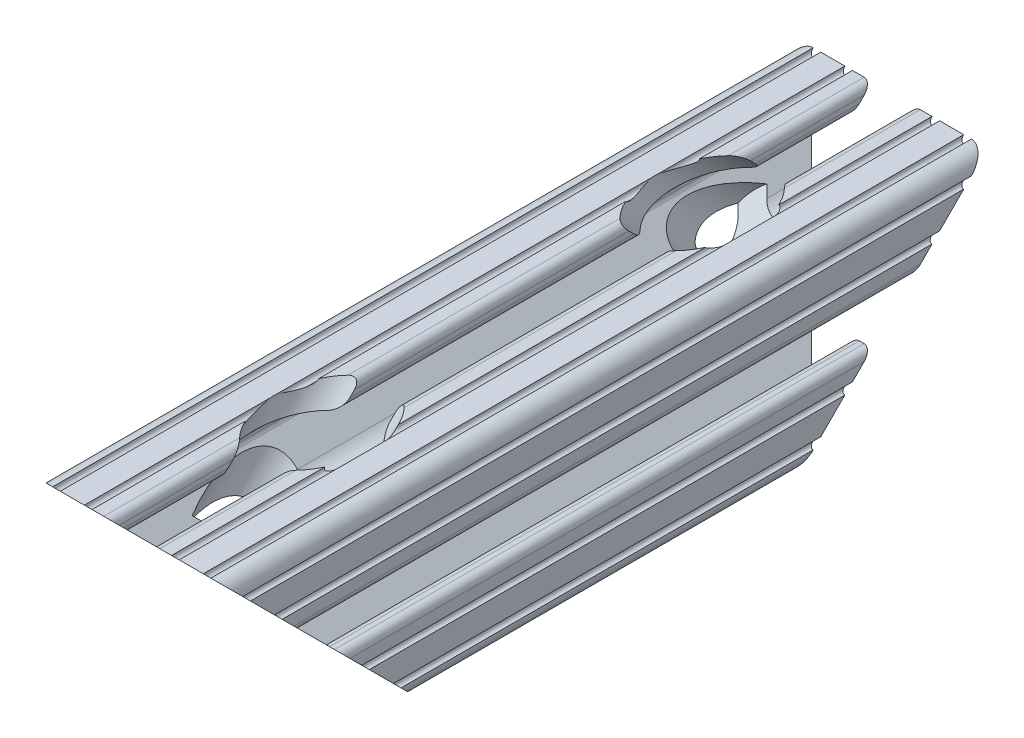
SolidWorks part; units mm, degrees
ref_plane "Front Plane" through (0, 0, 0) normal (0, 0, 1) x (1, 0, 0)
ref_plane "Top Plane" through (0, 0, 0) normal (0, 1, 0) x (1, 0, 0)
ref_plane "Right Plane" through (0, 0, 0) normal (1, 0, 0) x (0, 0, -1)
sketch "Sketch1" plane through (0, 0, 0) normal (0, 0, 1) x (1, 0, 0)
  line L2 (-10.287, 13.5524) -> (-10.287, 14.0843)
  line L3 (-9.3853, 14.986) -> (-5.6176, 14.986)
  line L4 (-4.064, 16.5396) -> (-4.064, 17.4964)
  line L6 (-5.6176, 19.05) -> (-7.9742, 19.05)
  line L7 (-9.4982, 19.05) -> (-14.3277, 19.05)
  line L8 (-19.05, 14.3277) -> (-19.05, 9.4961)
  line L9 (-19.05, 7.9763) -> (-19.05, 5.6176)
  line L10 (-17.4964, 4.064) -> (-16.5396, 4.064)
  line L11 (-14.986, 5.6176) -> (-14.986, 9.3853)
  line L12 (-14.0843, 10.287) -> (-13.516, 10.287)
  line L13 (-12.8784, 10.0229) -> (-8.1476, 5.2921)
  line L14 (-6.7564, 1.9335) -> (-6.7564, -1.9335)
  line L15 (-8.1476, -5.2921) -> (-12.8784, -10.0229)
  line L16 (-13.516, -10.287) -> (-14.0843, -10.287)
  line L17 (-14.986, -9.3853) -> (-14.986, -5.6176)
  line L18 (-16.5396, -4.064) -> (-17.4964, -4.064)
  line L19 (-19.05, -5.6176) -> (-19.05, -7.9763)
  line L20 (-19.05, -9.4961) -> (-19.05, -14.3277)
  line L21 (-14.3277, -19.05) -> (-9.4961, -19.05)
  line L22 (-7.9763, -19.05) -> (-5.6176, -19.05)
  line L23 (-4.064, -17.4964) -> (-4.064, -16.5396)
  line L24 (-5.6176, -14.986) -> (-9.3853, -14.986)
  line L25 (-10.287, -14.0843) -> (-10.287, -13.5524)
  line L26 (-10.0229, -12.9148) -> (-5.2522, -8.144)
  line L27 (-1.9022, -6.7564) -> (1.9022, -6.7564)
  line L28 (5.2522, -8.144) -> (10.0229, -12.9148)
  line L29 (10.287, -13.5524) -> (10.287, -14.0843)
  line L30 (9.3853, -14.986) -> (5.6176, -14.986)
  line L31 (4.064, -16.5396) -> (4.064, -17.4964)
  line L32 (5.6176, -19.05) -> (7.9763, -19.05)
  line L33 (9.4961, -19.05) -> (14.3277, -19.05)
  line L34 (19.05, -14.3277) -> (19.05, -9.4961)
  line L35 (19.05, -7.9763) -> (19.05, -5.6176)
  line L36 (17.4964, -4.064) -> (16.5396, -4.064)
  line L37 (14.986, -5.6176) -> (14.986, -9.3853)
  line L38 (14.0843, -10.287) -> (13.516, -10.287)
  line L39 (12.8784, -10.0229) -> (8.1476, -5.2921)
  line L40 (6.7564, -1.9335) -> (6.7564, 1.9335)
  line L41 (8.1476, 5.2921) -> (12.8784, 10.0229)
  line L42 (13.516, 10.287) -> (14.0843, 10.287)
  line L43 (14.986, 9.3853) -> (14.986, 5.6176)
  line L44 (16.5396, 4.064) -> (17.4964, 4.064)
  line L45 (19.05, 5.6176) -> (19.05, 7.9763)
  line L46 (19.05, 9.4961) -> (19.05, 14.3277)
  line L47 (14.3277, 19.05) -> (9.4982, 19.05)
  line L48 (7.9742, 19.05) -> (5.6176, 19.05)
  line L49 (4.064, 17.4964) -> (4.064, 16.5396)
  line L50 (5.6176, 14.986) -> (9.3853, 14.986)
  line L51 (10.287, 14.0843) -> (10.287, 13.5524)
  line L52 (10.0229, 12.9148) -> (5.2522, 8.144)
  line L53 (1.9022, 6.7564) -> (-1.9022, 6.7564)
  line L54 (-5.2522, 8.144) -> (-10.0229, 12.9148)
  circle A0 centre (0, 0) radius 3.3274
  arc A1 (-9.3853, 14.986) -> (-10.287, 14.0843) centre (-9.3853, 14.0843) ccw
  arc A2 (-5.6176, 14.986) -> (-4.064, 16.5396) centre (-5.6176, 16.5396) ccw
  arc A3 (-4.064, 17.4964) -> (-5.6176, 19.05) centre (-5.6176, 17.4964) ccw
  arc A4 (-9.4982, 19.05) -> (-7.9742, 19.05) centre (-8.7362, 19.05) ccw
  arc A5 (-15.8475, 19.05) -> (-14.3277, 19.05) centre (-15.0876, 18.9933) ccw
  arc A6 (-15.8475, 19.05) -> (-19.05, 15.8475) centre (-15.8751, 15.8751) ccw
  arc A7 (-19.05, 14.3277) -> (-19.05, 15.8475) centre (-18.9933, 15.0876) ccw
  arc A8 (-19.05, 7.9763) -> (-19.05, 9.4961) centre (-18.9933, 8.7362) ccw
  arc A9 (-19.05, 5.6176) -> (-17.4964, 4.064) centre (-17.4964, 5.6176) ccw
  arc A10 (-16.5396, 4.064) -> (-14.986, 5.6176) centre (-16.5396, 5.6176) ccw
  arc A11 (-14.0843, 10.287) -> (-14.986, 9.3853) centre (-14.0843, 9.3853) ccw
  arc A12 (-12.8784, 10.0229) -> (-13.516, 10.287) centre (-13.516, 9.3853) ccw
  arc A13 (-6.7564, 1.9335) -> (-8.1476, 5.2921) centre (-11.5062, 1.9335) ccw
  arc A14 (-8.1476, -5.2921) -> (-6.7564, -1.9335) centre (-11.5062, -1.9335) ccw
  arc A15 (-13.516, -10.287) -> (-12.8784, -10.0229) centre (-13.516, -9.3853) ccw
  arc A16 (-14.986, -9.3853) -> (-14.0843, -10.287) centre (-14.0843, -9.3853) ccw
  arc A17 (-14.986, -5.6176) -> (-16.5396, -4.064) centre (-16.5396, -5.6176) ccw
  arc A18 (-17.4964, -4.064) -> (-19.05, -5.6176) centre (-17.4964, -5.6176) ccw
  arc A19 (-19.05, -9.4961) -> (-19.05, -7.9763) centre (-18.9933, -8.7362) ccw
  arc A20 (-19.05, -15.8475) -> (-19.05, -14.3277) centre (-18.9933, -15.0876) ccw
  arc A21 (-19.05, -15.8475) -> (-15.8475, -19.05) centre (-15.8751, -15.8751) ccw
  arc A22 (-14.3277, -19.05) -> (-15.8475, -19.05) centre (-15.0876, -18.9933) ccw
  arc A23 (-7.9763, -19.05) -> (-9.4961, -19.05) centre (-8.7362, -18.9933) ccw
  arc A24 (-5.6176, -19.05) -> (-4.064, -17.4964) centre (-5.6176, -17.4964) ccw
  arc A25 (-4.064, -16.5396) -> (-5.6176, -14.986) centre (-5.6176, -16.5396) ccw
  arc A26 (-10.287, -14.0843) -> (-9.3853, -14.986) centre (-9.3853, -14.0843) ccw
  arc A27 (-10.0229, -12.9148) -> (-10.287, -13.5524) centre (-9.3853, -13.5524) ccw
  arc A28 (-1.9022, -6.7564) -> (-5.2522, -8.144) centre (-1.9022, -11.494) ccw
  arc A29 (5.2522, -8.144) -> (1.9022, -6.7564) centre (1.9022, -11.494) ccw
  arc A30 (10.287, -13.5524) -> (10.0229, -12.9148) centre (9.3853, -13.5524) ccw
  arc A31 (9.3853, -14.986) -> (10.287, -14.0843) centre (9.3853, -14.0843) ccw
  arc A32 (5.6176, -14.986) -> (4.064, -16.5396) centre (5.6176, -16.5396) ccw
  arc A33 (4.064, -17.4964) -> (5.6176, -19.05) centre (5.6176, -17.4964) ccw
  arc A34 (9.4961, -19.05) -> (7.9763, -19.05) centre (8.7362, -18.9933) ccw
  arc A35 (15.8475, -19.05) -> (14.3277, -19.05) centre (15.0876, -18.9933) ccw
  arc A36 (15.8475, -19.05) -> (19.05, -15.8475) centre (15.8751, -15.8751) ccw
  arc A37 (19.05, -14.3277) -> (19.05, -15.8475) centre (18.9933, -15.0876) ccw
  arc A38 (19.05, -7.9763) -> (19.05, -9.4961) centre (18.9933, -8.7362) ccw
  arc A39 (19.05, -5.6176) -> (17.4964, -4.064) centre (17.4964, -5.6176) ccw
  arc A40 (16.5396, -4.064) -> (14.986, -5.6176) centre (16.5396, -5.6176) ccw
  arc A41 (14.0843, -10.287) -> (14.986, -9.3853) centre (14.0843, -9.3853) ccw
  arc A42 (12.8784, -10.0229) -> (13.516, -10.287) centre (13.516, -9.3853) ccw
  arc A43 (6.7564, -1.9335) -> (8.1476, -5.2921) centre (11.5062, -1.9335) ccw
  arc A44 (8.1476, 5.2921) -> (6.7564, 1.9335) centre (11.5062, 1.9335) ccw
  arc A45 (13.516, 10.287) -> (12.8784, 10.0229) centre (13.516, 9.3853) ccw
  arc A46 (14.986, 9.3853) -> (14.0843, 10.287) centre (14.0843, 9.3853) ccw
  arc A47 (14.986, 5.6176) -> (16.5396, 4.064) centre (16.5396, 5.6176) ccw
  arc A48 (17.4964, 4.064) -> (19.05, 5.6176) centre (17.4964, 5.6176) ccw
  arc A49 (19.05, 9.4961) -> (19.05, 7.9763) centre (18.9933, 8.7362) ccw
  arc A50 (19.05, 15.8475) -> (19.05, 14.3277) centre (18.9933, 15.0876) ccw
  arc A51 (19.05, 15.8475) -> (15.8475, 19.05) centre (15.8751, 15.8751) ccw
  arc A52 (14.3277, 19.05) -> (15.8475, 19.05) centre (15.0876, 18.9933) ccw
  arc A53 (7.9742, 19.05) -> (9.4982, 19.05) centre (8.7362, 19.05) ccw
  arc A54 (5.6176, 19.05) -> (4.064, 17.4964) centre (5.6176, 17.4964) ccw
  arc A55 (4.064, 16.5396) -> (5.6176, 14.986) centre (5.6176, 16.5396) ccw
  arc A56 (10.287, 14.0843) -> (9.3853, 14.986) centre (9.3853, 14.0843) ccw
  arc A57 (10.0229, 12.9148) -> (10.287, 13.5524) centre (9.3853, 13.5524) ccw
  arc A58 (1.9022, 6.7564) -> (5.2522, 8.144) centre (1.9022, 11.494) ccw
  arc A59 (-5.2522, 8.144) -> (-1.9022, 6.7564) centre (-1.9022, 11.494) ccw
  arc A60 (-10.287, 13.5524) -> (-10.0229, 12.9148) centre (-9.3853, 13.5524) ccw
extrude "Boss-Extrude1" add sketch "Sketch1" along normal mid plane 152.4
sketch "Sketch2" plane through (0, 0, 0) normal (1, 0, 0) x (0, 0, -1)
  line L0 (-76.2, 19.05) -> (-76.2, -25.4)
  line L1 (-76.2, -25.4) -> (-31.75, -25.4)
  line L2 (-31.75, -25.4) -> (-76.2, 19.05)
  line L3 (0, 0) -> (0, -25.4) construction
  line L5 (31.75, -25.4) -> (76.2, 19.05)
  line L6 (76.2, -25.4) -> (31.75, -25.4)
  line L7 (76.2, 19.05) -> (76.2, -25.4)
  dimension "D1" = 25.4
extrude "Cut-Extrude1" cut sketch "Sketch2" against normal through all and the other way through all
sketch "Sketch3" plane through (0, 0, 0) normal (1, 0, 0) x (0, 0, -1)
  line L0 (-31.3648, 25.7852) -> (-57.15, 0)
  line L1 (-57.15, 0) -> (-59.4579, 2.3079)
  line L2 (-59.4579, 2.3079) -> (-54.9678, 6.7981)
  line L3 (-54.9678, 6.7981) -> (-59.3951, 11.2253)
  line L4 (-59.3951, 11.2253) -> (-38.1, 32.5204)
  line L5 (-38.1, 32.5204) -> (-31.3648, 25.7852)
  line L6 (-57.15, 0) -> (-59.4579, -2.3079) construction
  line L7 (-31.75, -25.4) -> (-76.2, 19.05) construction
  line L8 (-60.4774, 3.3274) -> (-53.8226, -3.3274) construction
  line L9 (-45.9247, -2.2451) -> (-24.6296, 19.05) construction
  dimension "D1" = 6.5278
  dimension "D2" = 19.05
  dimension "D3" = 6.35
revolve "Cut-Revolve1" cut sketch "Sketch3" angle 360 mid plane about L6
mirror "Mirror1" about plane through (0, 0, 0) normal (0, 0, 1) of "Cut-Revolve1"
